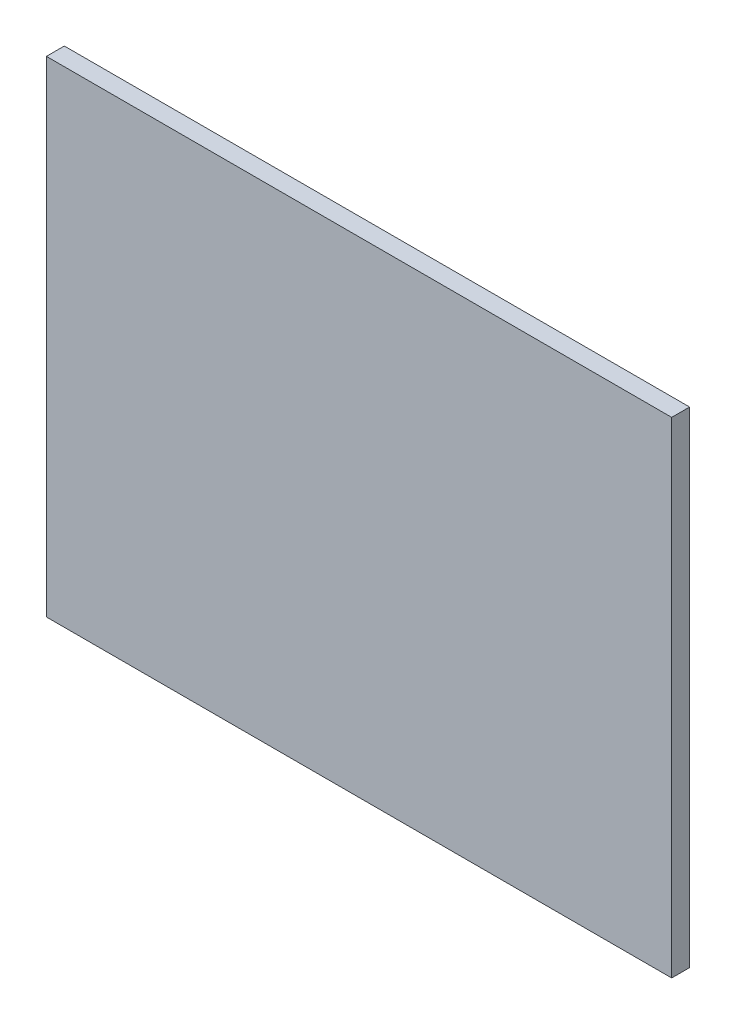
SolidWorks part; units mm, degrees
ref_plane "Plan de face" through (0, 0, 0) normal (0, 0, 1) x (1, 0, 0)
ref_plane "Plan de dessus" through (0, 0, 0) normal (0, 1, 0) x (1, 0, 0)
ref_plane "Plan de droite" through (0, 0, 0) normal (1, 0, 0) x (0, 0, -1)
sketch "Sketch2" plane through (0, 0, 0) normal (0, 0, 1) x (1, 0, 0)
  line L1 (0, 0) -> (69.8, 0)
  line L2 (0, 0) -> (0, 54.2)
  line L3 (0, 54.2) -> (69.8, 54.2)
  line L4 (69.8, 0) -> (69.8, 54.2)
  dimension "D1" = 54.2
  dimension "D2" = 69.8
extrude "Boss-Extrude3" add sketch "Sketch2" along normal blind 2
